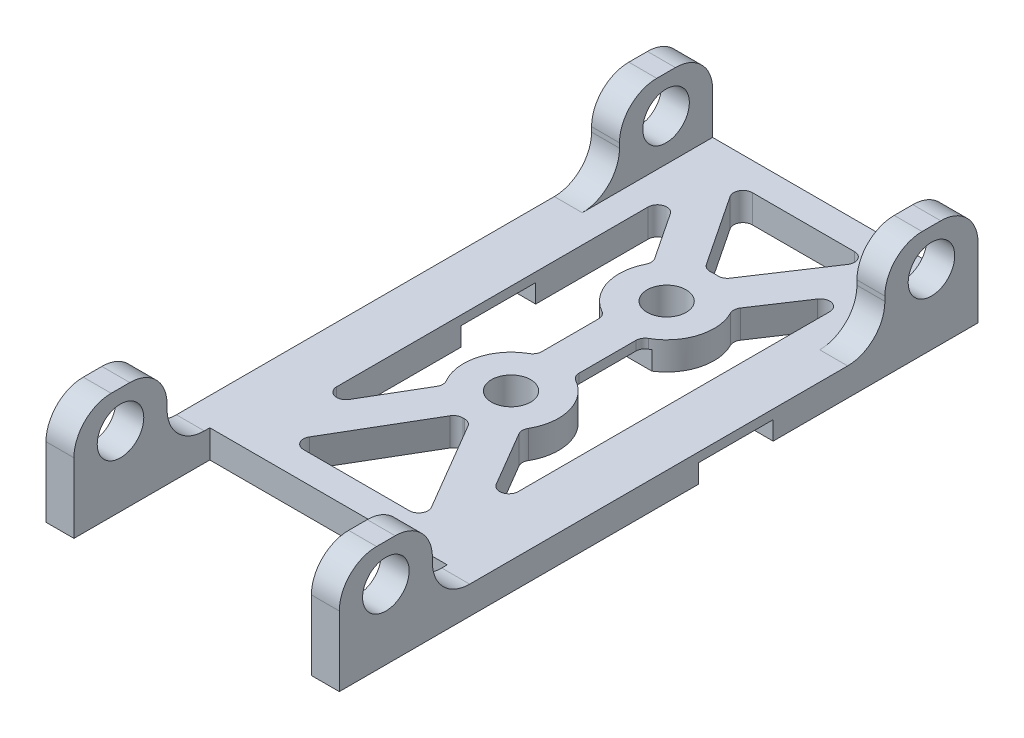
SolidWorks part; units mm, degrees
material "Thornel Mat VMA"
ref_plane "Front Plane" through (0, 0, 0) normal (0, 0, 1) x (1, 0, 0)
ref_plane "Top Plane" through (0, 0, 0) normal (0, 1, 0) x (1, 0, 0)
ref_plane "Right Plane" through (0, 0, 0) normal (1, 0, 0) x (0, 0, -1)
sketch "Sketch1" plane through (0, 0, 0) normal (1, 0, 0) x (0, 0, -1)
  line L1 (-6.1045, 0) -> (47.8955, 0)
  line L2 (-6.1045, 0) -> (-6.1045, 3)
  line L3 (-6.1045, 3) -> (47.8955, 3)
  line L4 (47.8955, 0) -> (47.8955, 3)
  dimension "D1" = 3
  dimension "D2" = 54
  dimension "D3" = 0
extrude "Boss-Extrude1" add sketch "Sketch1" along normal mid plane 25.5
sketch "Sketch2" plane through (0, 0, 0) normal (0, 1, 0) x (1, 0, 0)
  line L0 (12.75, -6.1045) -> (-12.75, -6.1045) construction
  line L1 (12.75, 47.8955) -> (15.75, 47.8955)
  line L2 (12.75, 47.8955) -> (12.75, -20.6945)
  line L3 (12.75, -20.6945) -> (15.75, -20.6945)
  line L4 (15.75, 47.8955) -> (15.75, -20.6945)
  line L7 (-15.75, 47.8955) -> (-15.75, -20.6945)
  line L8 (-12.75, -20.6945) -> (-15.75, -20.6945)
  line L9 (-12.75, 47.8955) -> (-12.75, -20.6945)
  line L10 (-12.75, 47.8955) -> (-15.75, 47.8955)
  dimension "D1" = 3
  dimension "D2" = 14.59
extrude "Boss-Extrude2" add sketch "Sketch2" along normal up to surface (3 mm away) up to face at (0, 3, -20.8955)
sketch "Sketch4" plane through (0, 3, 0) normal (0, 1, 0) x (1, 0, 0)
  circle A12 centre (0, 13.5) radius 2.1
  arc A13 (0.5104, 28.1725) -> (1.9898, 30.8807) centre (0, 30.2095) ccw
  arc A24 (1.9898, 30.8807) -> (-1.3499, 31.8182) centre (0, 30.2095) ccw
  arc A26 (-1.3499, 31.8182) -> (0.5104, 28.1725) centre (0, 30.2095) ccw
extrude "Cut-Extrude2" cut sketch "Sketch4" against normal up to surface (3 mm away) up to face at (0, 0, -0.1005)
sketch "Sketch5" plane through (0, 3, 0) normal (0, 1, 0) x (1, 0, 0)
  line L0 (-15.75, -20.6945) -> (-15.75, 47.8955) construction
  line L1 (-12.75, -20.6945) -> (-15.75, -20.6945)
  line L2 (-12.75, -20.6945) -> (-12.75, -10.6945)
  line L3 (-12.75, -10.6945) -> (-15.75, -10.6945)
  line L4 (-15.75, -20.6945) -> (-15.75, -10.6945)
  line L6 (15.75, -20.6945) -> (15.75, -10.6945)
  line L7 (12.75, -10.6945) -> (15.75, -10.6945)
  line L8 (12.75, -20.6945) -> (12.75, -10.6945)
  line L9 (12.75, -20.6945) -> (15.75, -20.6945)
  line L10 (12.75, 47.8955) -> (15.75, 47.8955)
  line L11 (12.75, 47.8955) -> (12.75, 37.8955)
  line L12 (12.75, 37.8955) -> (15.75, 37.8955)
  line L13 (15.75, 47.8955) -> (15.75, 37.8955)
  line L14 (-15.75, 47.8955) -> (-15.75, 37.8955)
  line L15 (-12.75, 37.8955) -> (-15.75, 37.8955)
  line L16 (-12.75, 47.8955) -> (-12.75, 37.8955)
  line L17 (-12.75, 47.8955) -> (-15.75, 47.8955)
  dimension "D1" = 10
extrude "Boss-Extrude3" add sketch "Sketch5" along normal blind 8.5
sketch "Sketch6" plane through (0, 0, 0) normal (0, -1, 0) x (1, 0, 0)
  line L0 (-15.75, -47.8955) -> (-15.75, 20.6945) construction
  line L1 (-15.75, -17.8955) -> (15.75, -17.8955)
  line L2 (-15.75, -17.8955) -> (-15.75, -25.8955)
  line L3 (-15.75, -25.8955) -> (15.75, -25.8955)
  line L4 (15.75, -17.8955) -> (15.75, -25.8955)
  line L5 (15.75, 20.6945) -> (15.75, -47.8955) construction
  line L6 (15.75, -47.8955) -> (-15.75, -47.8955) construction
  dimension "D1" = 8
  dimension "D2" = 22
extrude "Cut-Extrude3" cut sketch "Sketch6" against normal blind 2
fillet "Fillet1" radius 4 12 edges at (14.25, 3, -37.8955) (-14.25, 3, -37.8955) (-14.25, 3, 10.6945) (14.25, 3, 10.6945) (14.25, 11.5, 10.6945) (14.25, 11.5, 20.6945) (-14.25, 11.5, 20.6945) (-14.25, 11.5, 10.6945) (14.25, 11.5, -47.8955) (14.25, 11.5, -37.8955) (-14.25, 11.5, -47.8955) (-14.25, 11.5, -37.8955)
sketch "Sketch7" plane through (0, 3, 0) normal (0, 1, 0) x (1, 0, 0)
  line L2 (0.9647, 7.9072) -> (6.5462, -1.5981)
  line L4 (-4.6039, 33.5283) -> (-7.9169, 38.5184)
  line L5 (1.2715, 35.7407) -> (6.3183, 43.3424)
  line L8 (4.6039, 33.5283) -> (7.9169, 38.5184)
  line L16 (-5.4852, 44.8955) -> (5.4852, 44.8955)
  line L17 (9.75, 37.9653) -> (9.75, 4.5233)
  line L18 (5.6838, -3.1045) -> (-5.6838, -3.1045)
  line L19 (-9.75, 4.5233) -> (-9.75, 37.9653)
  line L26 (-2, 18.8113) -> (-2, 24.8982)
  line L28 (4.414, 9.9326) -> (7.8877, 4.017)
  line L29 (-7.8877, 4.017) -> (-4.414, 9.9326)
  line L30 (2, 18.8113) -> (2, 24.8982)
  line L31 (-1.2715, 35.7407) -> (-6.3183, 43.3424)
  line L34 (-6.5462, -1.5981) -> (-0.9647, 7.9072)
  arc A0 (-4.5457, 32.5218) -> (-2.5082, 25.7689) centre (0, 30.2095) ccw
  arc A1 (0.3665, 35.2963) -> (-0.3665, 35.2963) centre (0, 30.2095) ccw
  circle A2 centre (0, 13.5) radius 5.1
  arc A3 (4.4114, 10.9408) -> (2.5082, 17.9406) centre (0, 13.5) ccw
  arc A4 (-0.0856, 8.4007) -> (0.0856, 8.4007) centre (0, 13.5) ccw
  circle A5 centre (0, 30.2095) radius 5.1
  arc A6 (2.5082, 25.7689) -> (4.5457, 32.5218) centre (0, 30.2095) ccw
  arc A7 (-2.5082, 17.9406) -> (-4.4114, 10.9408) centre (0, 13.5) ccw
  arc A8 (4.6039, 33.5283) -> (4.5457, 32.5218) centre (5.437, 32.9752) ccw
  arc A9 (9.75, 37.9653) -> (7.9169, 38.5184) centre (8.75, 37.9653) ccw
  arc A10 (2.5082, 25.7689) -> (2, 24.8982) centre (3, 24.8982) ccw
  arc A11 (2, 18.8113) -> (2.5082, 17.9406) centre (3, 18.8113) ccw
  arc A12 (4.4114, 10.9408) -> (4.414, 9.9326) centre (5.2764, 10.439) ccw
  arc A13 (9.75, 4.5233) -> (7.8877, 4.017) centre (8.75, 4.5233) cw
  arc A14 (6.5462, -1.5981) -> (5.6838, -3.1045) centre (5.6838, -2.1045) cw
  arc A15 (0.9647, 7.9072) -> (0.0856, 8.4007) centre (0.1024, 7.4009) ccw
  arc A16 (-0.9647, 7.9072) -> (-0.0856, 8.4007) centre (-0.1024, 7.4009) cw
  arc A17 (-5.6838, -3.1045) -> (-6.5462, -1.5981) centre (-5.6838, -2.1045) cw
  arc A18 (-4.4114, 10.9408) -> (-4.414, 9.9326) centre (-5.2764, 10.439) cw
  arc A19 (-9.75, 4.5233) -> (-7.8877, 4.017) centre (-8.75, 4.5233) ccw
  arc A20 (-2, 18.8113) -> (-2.5082, 17.9406) centre (-3, 18.8113) cw
  arc A21 (-2, 24.8982) -> (-2.5082, 25.7689) centre (-3, 24.8982) ccw
  arc A22 (-4.6039, 33.5283) -> (-4.5457, 32.5218) centre (-5.437, 32.9752) cw
  arc A23 (-9.75, 37.9653) -> (-7.9169, 38.5184) centre (-8.75, 37.9653) cw
  arc A24 (1.2715, 35.7407) -> (0.3665, 35.2963) centre (0.4384, 36.2938) cw
  arc A25 (-1.2715, 35.7407) -> (-0.3665, 35.2963) centre (-0.4384, 36.2938) ccw
  arc A26 (5.4852, 44.8955) -> (6.3183, 43.3424) centre (5.4852, 43.8955) cw
  arc A27 (-5.4852, 44.8955) -> (-6.3183, 43.3424) centre (-5.4852, 43.8955) ccw
  point P38 (0.6509, 8.4417)
  point P43 (-0.6509, 8.4417)
  point P52 (-2, 18.1915)
  point P55 (-2, 25.5181)
  point P58 (-4.2611, 33.0119)
  point P63 (0.9286, 35.2243)
  dimension "D3" = 1
  dimension "D1" = 3
  dimension "D2" = 3
extrude "Cut-Extrude4" cut sketch "Sketch7" against normal through all both and the other way through all
sketch "Sketch8" plane through (15.75, 0, 0) normal (1, 0, 0) x (0, 0, -1)
  circle A0 centre (-15.6945, 7.5) radius 2.5
  circle A1 centre (42.8955, 7.5) radius 2.5
  dimension "D1" = 5
extrude "Cut-Extrude5" cut sketch "Sketch8" against normal through all both and the other way through all
